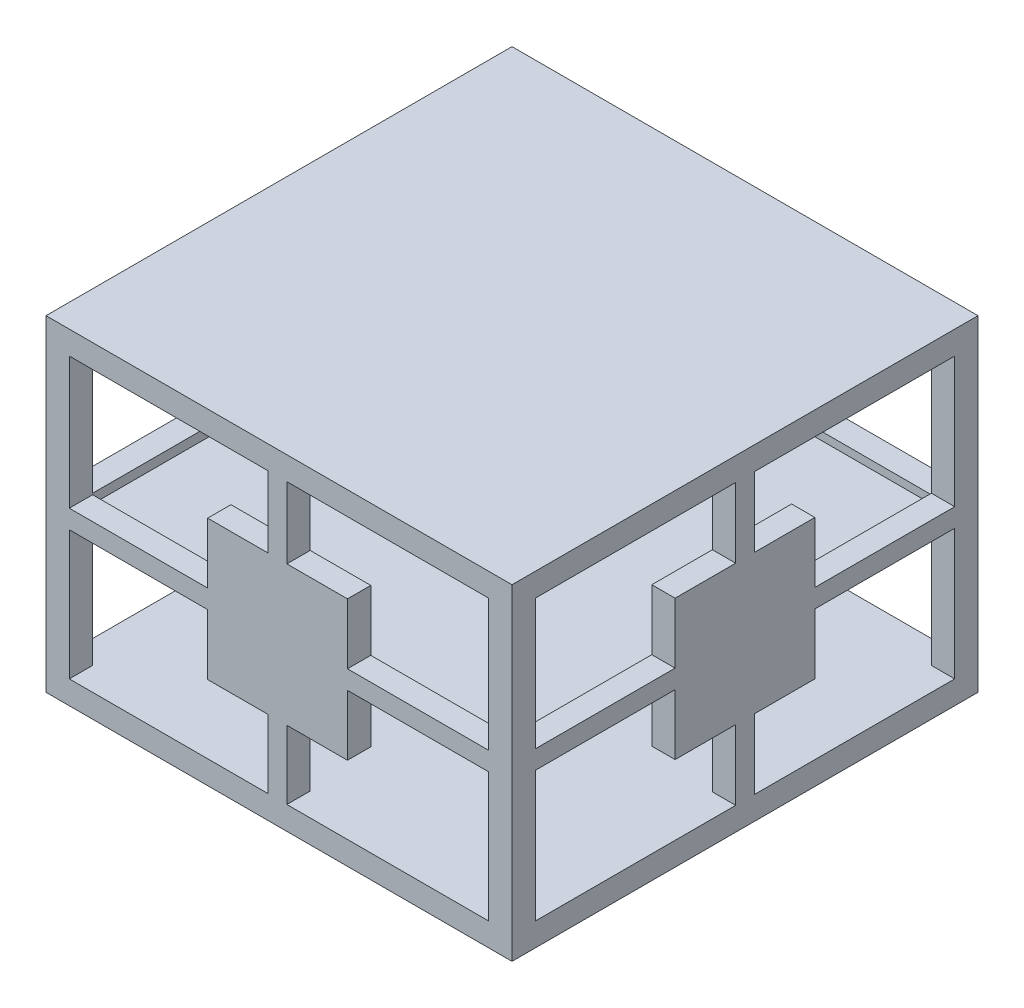
SolidWorks part; units mm, degrees
material "Acrylic (Medium-high impact)"
ref_plane "Front Plane" through (0, 0, 0) normal (0, 0, 1) x (1, 0, 0)
ref_plane "Top Plane" through (0, 0, 0) normal (0, 1, 0) x (1, 0, 0)
ref_plane "Right Plane" through (0, 0, 0) normal (1, 0, 0) x (0, 0, -1)
sketch "Sketch1" plane through (0, 0, 0) normal (0, 1, 0) x (1, 0, 0)
  line L1 (-100, -100) -> (100, -100)
  line L2 (-100, -100) -> (-100, 100)
  line L3 (-100, 100) -> (100, 100)
  line L4 (100, -100) -> (100, 100)
  line L5 (-100, -100) -> (100, 100) construction
  line L6 (-100, 100) -> (100, -100) construction
  point P0 (0, 0)
  dimension "D1" = 200
  dimension "D2" = 200
extrude "Boss-Extrude1" add sketch "Sketch1" along normal blind 140
shell "Shell2" thickness 10
sketch "Sketch2" plane through (100, 0, 0) normal (1, 0, 0) x (0, 0, -1)
  line L0 (-100, 140) -> (-100, 0) construction
  line L1 (-30, 40) -> (-4, 40)
  line L2 (-30, 40) -> (-30, 66)
  line L3 (-30, 100) -> (-4, 100)
  line L4 (30, 40) -> (30, 66)
  line L5 (30, 74) -> (30, 100)
  line L6 (4, 40) -> (30, 40)
  line L7 (-4, 40) -> (-4, 10)
  line L8 (-30, 74) -> (-30, 100)
  line L9 (90, 74) -> (30, 74)
  line L10 (90, 66) -> (30, 66)
  line L11 (4, 40) -> (4, 10)
  line L12 (4, 100) -> (30, 100)
  line L13 (-90, 130) -> (-90, 74)
  line L14 (-4, 130) -> (-4, 100)
  line L15 (4, 130) -> (4, 100)
  line L16 (4, 130) -> (90, 130)
  line L17 (-90, 66) -> (-90, 10)
  line L18 (4, 10) -> (90, 10)
  line L19 (90, 66) -> (90, 10)
  line L20 (-30, 74) -> (-90, 74)
  line L21 (-30, 66) -> (-90, 66)
  line L22 (-90, 10) -> (-4, 10)
  line L23 (90, 130) -> (90, 74)
  line L24 (-90, 130) -> (-4, 130)
  point P0 (0, 70)
  point P5 (-100, 70)
  dimension "D1" = 60
  dimension "D2" = 60
  dimension "D3" = 0
  dimension "D4" = 0
sketch "Sketch3" plane through (0, 0, 100) normal (0, 0, 1) x (1, 0, 0)
  line L0 (-30.6163, 39.4385) -> (-4.6163, 39.4385)
  line L1 (-30.6163, 39.4385) -> (-30.6163, 65.4385)
  line L2 (-30.6163, 99.4385) -> (-4.6163, 99.4385)
  line L3 (29.3837, 39.4385) -> (29.3837, 65.4385)
  line L4 (29.3837, 73.4385) -> (29.3837, 99.4385)
  line L5 (3.3837, 39.4385) -> (29.3837, 39.4385)
  line L6 (-4.6163, 39.4385) -> (-4.6163, 10)
  line L7 (-30.6163, 73.4385) -> (-30.6163, 99.4385)
  line L8 (90, 73.4385) -> (29.3837, 73.4385)
  line L9 (90, 65.4385) -> (29.3837, 65.4385)
  line L10 (3.3837, 39.4385) -> (3.3837, 10)
  line L11 (3.3837, 99.4385) -> (29.3837, 99.4385)
  line L12 (-4.6163, 130) -> (-4.6163, 99.4385)
  line L13 (3.3837, 130) -> (3.3837, 99.4385)
  line L14 (-30.6163, 73.4385) -> (-90, 73.4385)
  line L15 (-30.6163, 65.4385) -> (-90, 65.4385)
  line L16 (-90, 130) -> (-90, 73.4385)
  line L17 (-100, 0) -> (100, 0) construction
  line L18 (90, 65.4385) -> (90, 10)
  line L19 (-4.6163, 0) -> (3.3837, 0)
  line L21 (-90, 10) -> (-4.6163, 10)
  line L22 (90, 130) -> (90, 73.4385)
  line L23 (-90, 130) -> (-4.6163, 130)
  line L24 (-100, 140) -> (100, 140) construction
  line L25 (-100, 140) -> (-100, 0) construction
  line L26 (-100, 73.4385) -> (-100.6163, 73.4385)
  line L27 (-100, 65.4385) -> (-100.6163, 65.4385)
  line L28 (-90, 65.4385) -> (-90, 10)
  line L29 (-90, 130) -> (-90, 10) construction
  line L30 (-4.6163, 0) -> (-4.6163, -0.5615)
  line L31 (3.3837, 0) -> (3.3837, -0.5615)
  line L32 (100, 140) -> (100, 0) construction
  line L33 (90, 130) -> (90, 10) construction
  line L34 (3.3837, 130) -> (90, 130)
  line L35 (-90, 130) -> (90, 130) construction
  line L36 (3.3837, 10) -> (90, 10)
  line L37 (-90, 10) -> (90, 10) construction
  point P0 (0, 70)
  dimension "D1" = 10
extrude "Cut-Extrude2" cut sketch "Sketch2" against normal through all
extrude "Cut-Extrude3" cut sketch "Sketch3" against normal through all contours L10 L36 L18 L9 L3 L5 | L34 L13 L11 L4 L8 L22 | L23 L16 L14 L7 L2 L12 | L15 L28 L21 L6 L0 L1
sketch "Sketch4" plane through (29.3072, 70, -14.7204) normal (0, 1, 0) x (1, 0, 0)
  line L1 (60.6928, 75.2796) -> (-119.3072, 75.2796)
  line L2 (60.6928, 75.2796) -> (60.6928, -104.7204)
  line L3 (60.6928, -104.7204) -> (-119.3072, -104.7204)
  line L4 (-119.3072, 75.2796) -> (-119.3072, -104.7204)
extrude "Boss-Extrude3" add sketch "Sketch4" against normal blind 4
